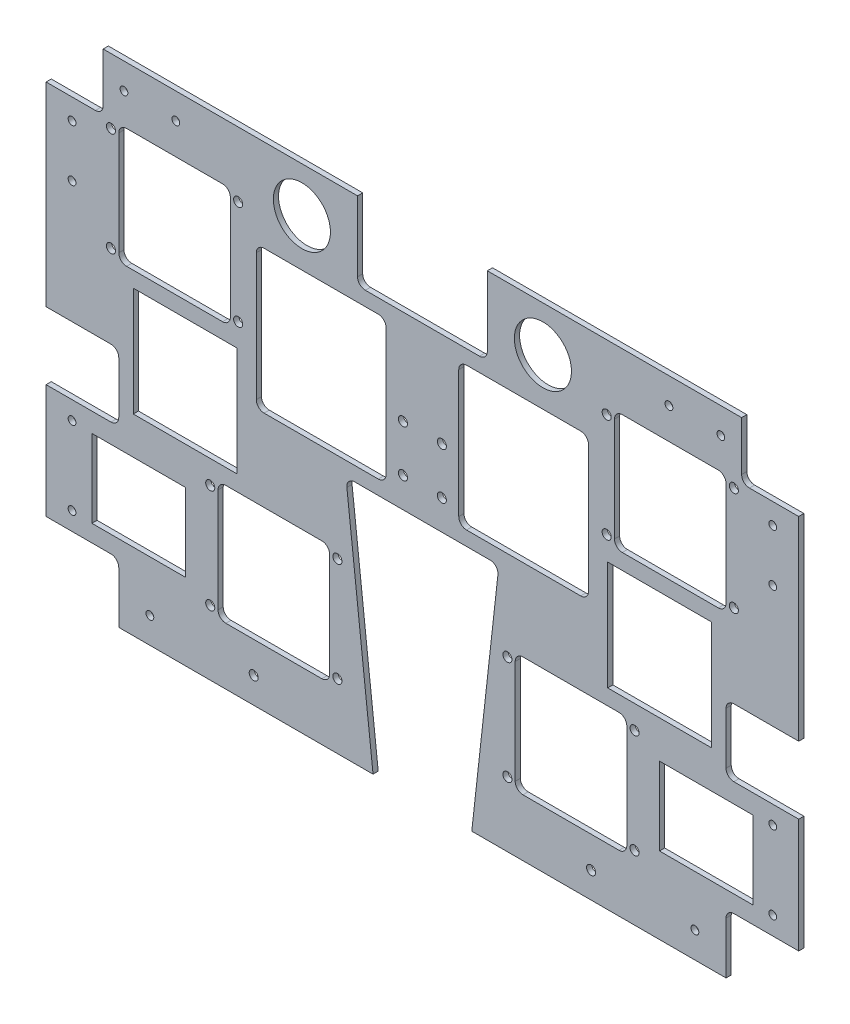
SolidWorks part; units mm, degrees
material "水绿环氧树脂"
ref_plane "前视基准面" through (0, 0, 0) normal (0, 0, 1) x (1, 0, 0)
ref_plane "上视基准面" through (0, 0, 0) normal (0, 1, 0) x (1, 0, 0)
ref_plane "右视基准面" through (0, 0, 0) normal (1, 0, 0) x (0, 0, -1)
sketch "草图1" plane through (0, 0, 0) normal (0, 0, 1) x (1, 0, 0)
  line L1 (-145, -95) -> (145, -95)
  line L2 (-145, -95) -> (-145, 95)
  line L3 (-145, 95) -> (145, 95)
  line L4 (145, -95) -> (145, 95)
  line L5 (-145, -95) -> (145, 95) construction
  line L6 (-145, 95) -> (145, -95) construction
  point P0 (0, 0)
  dimension "D1" = 190
  dimension "D2" = 290
extrude "凸台-拉伸1" add sketch "草图1" along normal blind 2
sketch "草图2" plane through (0, 0, 0) normal (0, 0, -1) x (-1, 0, 0)
  line L6 (-145, 95) -> (-123, 95)
  line L7 (-145, 95) -> (-145, 73)
  line L8 (-145, 73) -> (-123, 73)
  line L9 (-123, 95) -> (-123, 73)
  line L18 (145, 95) -> (123, 95)
  line L19 (-125, -72) -> (-145, -72)
  line L20 (-145, -95) -> (-145, 95) construction
  line L21 (-145, -72) -> (-145, -111.8697)
  line L22 (-145, -111.8697) -> (-117, -111.8697)
  line L23 (-117, -111.8697) -> (-117, -72)
  line L24 (-117, -72) -> (-125, -72)
  line L25 (0, -95) -> (0, -53.3628) construction
  line L26 (145, -95) -> (-145, -95) construction
  line L27 (117, -72) -> (125, -72)
  line L28 (117, -111.8697) -> (117, -72)
  line L29 (145, -111.8697) -> (117, -111.8697)
  line L30 (145, -72) -> (145, -111.8697)
  line L31 (125, -72) -> (145, -72)
  line L32 (145, 95) -> (145, 73)
  line L38 (145, 73) -> (123, 73)
  line L39 (123, 95) -> (123, 73)
  dimension "D1" = 22
  dimension "D2" = 22
  dimension "D7" = 28
extrude "切除-拉伸1" cut sketch "草图2" against normal blind 2
fillet "圆角2" radius 3 2 edges at (-117, -72, 1) (117, -72, 1)
fillet "圆角3" radius 3 2 edges at (123, 73, 1) (-123, 73, 1)
sketch "草图3" plane through (0, 0, 2) normal (0, 0, 1) x (1, 0, 0)
  line L0 (0, 95) -> (25, 95) construction
  line L1 (123, 95) -> (-123, 95) construction
  line L2 (25, 95) -> (25, 65)
  line L3 (25, 65) -> (-25, 65)
  line L4 (-25, 65) -> (-25, 95)
  line L5 (-25, 95) -> (25, 95)
  dimension "D1" = 25
  dimension "D2" = 30
  dimension "D3" = 50
extrude "切除-拉伸2" cut sketch "草图3" against normal blind 10
fillet "圆角4" radius 3 2 edges at (25, 65, 1) (-25, 65, 1)
sketch "草图4" plane through (0, 0, 0) normal (0, 0, -1) x (-1, 0, 0)
  line L6 (18.9755, -95.4417) -> (29.4691, -1)
  line L7 (29.4691, -1) -> (-29.4691, -1)
  line L8 (-29.4691, -1) -> (-18.9755, -95.4417)
  line L9 (18.9755, -95.4417) -> (-18.9755, -95.4417)
extrude "切除-拉伸3" cut sketch "草图4" against normal blind 10
fillet "圆角5" radius 3 2 edges at (-29.4691, -1, 1) (29.4691, -1, 1)
sketch "草图5" plane through (0, 0, 0) normal (0, 0, -1) x (-1, 0, 0)
  circle A15 centre (-105, -85) radius 1.5
  circle A16 centre (105, -85) radius 1.5
  circle A17 centre (135, 45) radius 1.5
  circle A18 centre (135, 65) radius 1.5
  circle A19 centre (115, 85) radius 1.5
  circle A20 centre (-115, 85) radius 1.5
  circle A21 centre (-135, 65) radius 1.5
  circle A22 centre (-135, 45) radius 1.5
  circle A23 centre (-95, 85) radius 1.5
  circle A24 centre (-135, -35) radius 1.5
  circle A25 centre (-135, -65) radius 1.5
  circle A26 centre (135, -65) radius 1.5
  circle A27 centre (135, -35) radius 1.5
  circle A28 centre (135, 45) radius 1.5
  circle A29 centre (95, 85) radius 1.5
  circle A32 centre (65, -85) radius 1.75
  circle A33 centre (-65, -85) radius 1.75
extrude "切除-拉伸4" cut sketch "草图5" against normal blind 10 contours A32 | A16 | A27 | A33 | A25 | A24 | A22 | A21 | A20 | A23 | A29 | A19 | A18 | A17 | A26 | A15
sketch "草图6" plane through (0, 0, 0) normal (0, 0, -1) x (-1, 0, 0)
  line L8 (125, -2) -> (117, -2) construction
  line L9 (-125, -2) -> (-117, -2) construction
  line L11 (117, -2) -> (155.3679, -2)
  line L12 (117, -2) -> (117, -28)
  line L13 (117, -28) -> (155.3679, -28)
  line L14 (155.3679, -2) -> (155.3679, -28)
  line L15 (-117, -2) -> (-160.939, -2)
  line L16 (-117, -2) -> (-117, -28)
  line L17 (-117, -28) -> (-160.939, -28)
  line L18 (-160.939, -2) -> (-160.939, -28)
  dimension "D5" = 8
  dimension "D6" = 8
extrude "切除-拉伸5" cut sketch "草图6" against normal blind 10
fillet "圆角6" radius 3 4 edges at (117, -28, 1) (117, -2, 1) (-117, -28, 1) (-117, -2, 1)
sketch "草图7" plane through (0, 0, 0) normal (0, 0, -1) x (-1, 0, 0)
  circle A16 centre (81.75, -70) radius 1.75
  circle A17 centre (32.75, -70) radius 1.75
  circle A18 centre (32.75, -30) radius 1.75
  circle A19 centre (81.75, -30) radius 1.75
  circle A20 centre (-81.75, -70) radius 1.75
  circle A21 centre (-32.75, -70) radius 1.75
  circle A22 centre (-32.75, -30) radius 1.75
  circle A23 centre (-81.75, -30) radius 1.75
  circle A24 centre (-120, 30) radius 1.75
  circle A25 centre (-120, 70) radius 1.75
  circle A26 centre (-71, 70) radius 1.75
  circle A27 centre (-71, 30) radius 1.75
  circle A28 centre (71, 70) radius 1.75
  circle A29 centre (120, 30) radius 1.75
  circle A30 centre (71, 30) radius 1.75
  circle A31 centre (120, 70) radius 1.75
extrude "切除-拉伸6" cut sketch "草图7" against normal blind 10
sketch "草图8" plane through (0, 0, 0) normal (0, 0, -1) x (-1, 0, 0)
  line L0 (-120, 70) -> (-120, 30) construction
  line L1 (-120, 50) -> (-95.5, 50) construction
  line L2 (-81.75, -70) -> (-81.75, -30) construction
  line L3 (-117, 27) -> (-74, 27)
  line L4 (-117, 27) -> (-117, 73)
  line L5 (-117, 73) -> (-74, 73)
  line L6 (-74, 27) -> (-74, 73)
  line L7 (-117, 27) -> (-74, 73) construction
  line L8 (-117, 73) -> (-74, 27) construction
  line L9 (-81.75, -50) -> (-57.25, -50) construction
  line L10 (0, 65) -> (0, -129.4612) construction
  line L11 (-78.75, -73) -> (-35.75, -73)
  line L12 (-78.75, -73) -> (-78.75, -27)
  line L13 (-78.75, -27) -> (-35.75, -27)
  line L14 (-35.75, -73) -> (-35.75, -27)
  line L15 (-78.75, -73) -> (-35.75, -27) construction
  line L16 (-78.75, -27) -> (-35.75, -73) construction
  line L17 (-22, 65) -> (22, 65) construction
  line L18 (78.75, -27) -> (35.75, -73) construction
  line L19 (78.75, -73) -> (35.75, -27) construction
  line L20 (81.75, -50) -> (57.25, -50) construction
  line L21 (117, 73) -> (74, 27) construction
  line L22 (117, 27) -> (74, 73) construction
  line L23 (81.75, -70) -> (81.75, -30) construction
  line L24 (120, 50) -> (95.5, 50) construction
  line L25 (120, 70) -> (120, 30) construction
  line L26 (35.75, -73) -> (35.75, -27)
  line L27 (78.75, -27) -> (35.75, -27)
  line L28 (78.75, -73) -> (78.75, -27)
  line L29 (78.75, -73) -> (35.75, -73)
  line L30 (74, 27) -> (74, 73)
  line L31 (117, 73) -> (74, 73)
  line L32 (117, 27) -> (117, 73)
  line L33 (117, 27) -> (74, 27)
  dimension "D1" = 24.5
  dimension "D2" = 46
  dimension "D3" = 43
  dimension "D4" = 24.5
  dimension "D5" = 46
  dimension "D6" = 43
extrude "切除-拉伸7" cut sketch "草图8" against normal blind 10
fillet "圆角7" radius 3 16 edges at (117, 27, 1) (78.75, -73, 1) (78.75, -27, 1) (35.75, -27, 1) (35.75, -73, 1) (-35.75, -73, 1) (-35.75, -27, 1) (-78.75, -27, 1) (-78.75, -73, 1) (-74, 27, 1) (-74, 73, 1) (-117, 73, 1) (-117, 27, 1) (74, 27, 1) (74, 73, 1) (117, 73, 1)
sketch "草图9" plane through (0, 0, 0) normal (0, 0, -1) x (-1, 0, 0)
  line L0 (0, 65) -> (0, -1) construction
  line L1 (22, 65) -> (-22, 65) construction
  line L2 (26.1173, -1) -> (-26.1173, -1) construction
  line L3 (-14, 59.5) -> (-64, 59.5)
  line L4 (64, 4.5) -> (14, 4.5)
  line L5 (64, 4.5) -> (64, 59.5)
  line L6 (64, 59.5) -> (14, 59.5)
  line L7 (-64, 4.5) -> (-64, 59.5)
  line L8 (64, 4.5) -> (14, 25.9844) construction
  line L9 (64, 59.5) -> (14, 38.0156) construction
  line L11 (14, 4.5) -> (14, 59.5)
  line L13 (-14, 4.5) -> (-14, 59.5)
  line L16 (-14, 25.9844) -> (-64, 4.5) construction
  line L17 (-14, 38.0156) -> (-64, 59.5) construction
  line L18 (-14, 4.5) -> (-64, 4.5)
  point P0 (0, 32)
  point P8 (0, 32)
  dimension "D1" = 55
  dimension "D2" = 128
  dimension "D3" = 55
  dimension "D4" = 28
sketch "草图10" plane through (0, 0, 2) normal (0, 0, 1) x (1, 0, 0)
  line L0 (0, 65) -> (0, -48.4291) construction
  line L1 (71.3962, -21) -> (111.3962, -21)
  line L2 (71.3962, -21) -> (71.3962, 21)
  line L3 (71.3962, 21) -> (111.3962, 21)
  line L4 (111.3962, -21) -> (111.3962, 21)
  line L5 (71.3962, -21) -> (111.3962, 21) construction
  line L6 (71.3962, 21) -> (111.3962, -21) construction
  line L7 (-22, 65) -> (22, 65) construction
  line L8 (-71.3962, 21) -> (-111.3962, -21) construction
  line L9 (-71.3962, -21) -> (-111.3962, 21) construction
  line L10 (-111.3962, -21) -> (-111.3962, 21)
  line L11 (-71.3962, 21) -> (-111.3962, 21)
  line L12 (-71.3962, -21) -> (-71.3962, 21)
  line L13 (-71.3962, -21) -> (-111.3962, -21)
  line L14 (-91.3528, -35.4436) -> (-127.3528, -35.4436)
  line L15 (91.3528, -65.4436) -> (127.3528, -65.4436)
  line L16 (91.3528, -65.4436) -> (91.3528, -35.4436)
  line L17 (91.3528, -35.4436) -> (127.3528, -35.4436)
  line L18 (127.3528, -65.4436) -> (127.3528, -35.4436)
  line L19 (91.3528, -65.4436) -> (127.3528, -35.4436) construction
  line L20 (91.3528, -35.4436) -> (127.3528, -65.4436) construction
  line L21 (-127.3528, -65.4436) -> (-127.3528, -35.4436)
  line L22 (-91.3528, -65.4436) -> (-127.3528, -65.4436)
  line L23 (-91.3528, -65.4436) -> (-91.3528, -35.4436)
  line L24 (-91.3528, -35.4436) -> (-127.3528, -65.4436) construction
  line L25 (-91.3528, -65.4436) -> (-127.3528, -35.4436) construction
  circle A0 centre (-46.436, 77.6674) radius 11
  circle A1 centre (46.436, 77.6674) radius 11
  point P0 (91.3962, 0)
  point P14 (-91.3962, 0)
  point P15 (109.3528, -50.4436)
  point P24 (-109.3528, -50.4436)
  dimension "D5" = 22
  dimension "D1" = 42
  dimension "D2" = 40
  dimension "D3" = 30
  dimension "D4" = 36
extrude "切除-拉伸9" cut sketch "草图10" against normal blind 10
sketch "草图11" plane through (0, 0, 0) normal (0, 0, -1) x (-1, 0, 0)
  circle A4 centre (7.5, 10.5) radius 1.75
  circle A5 centre (-7.5, 10.5) radius 1.75
  circle A6 centre (7.5, 28.5) radius 1.75
  circle A7 centre (-7.5, 28.5) radius 1.75
extrude "切除-拉伸10" cut sketch "草图11" against normal blind 10
extrude "切除-拉伸11" cut sketch "草图9" against normal blind 10
fillet "圆角8" radius 3 8 edges at (64, 4.5, 1) (64, 59.5, 1) (14, 4.5, 1) (14, 59.5, 1) (-14, 4.5, 1) (-64, 4.5, 1) (-14, 59.5, 1) (-64, 59.5, 1)
